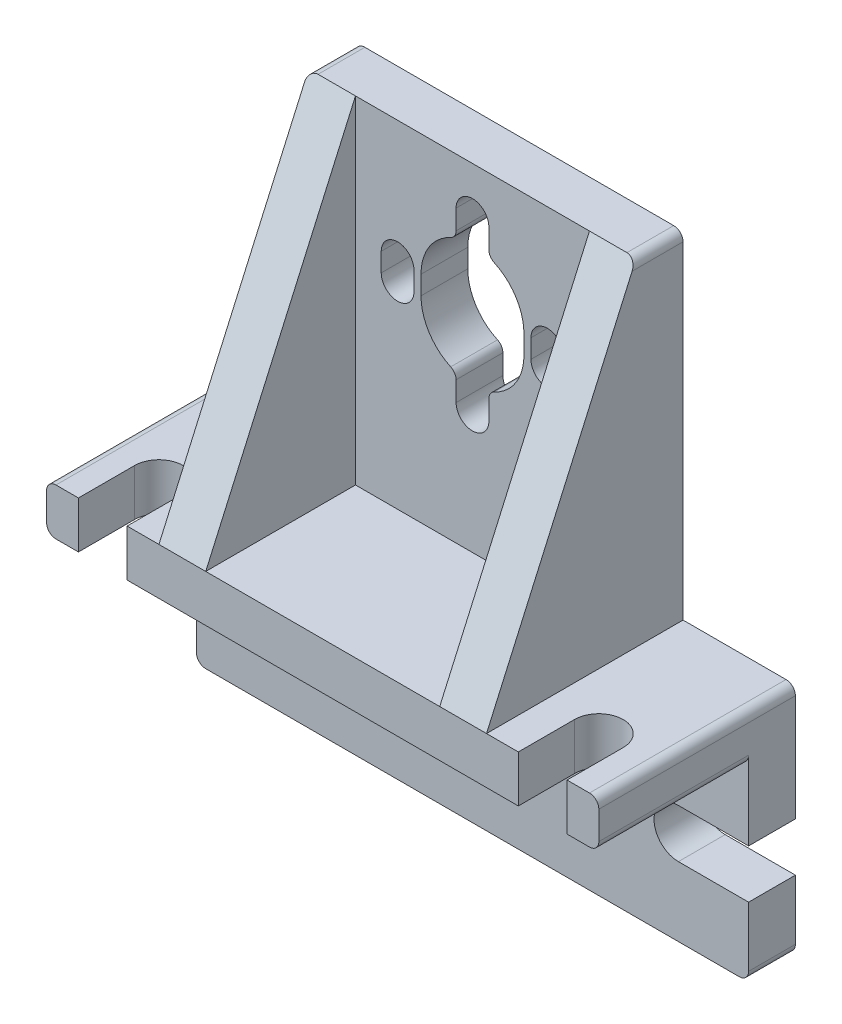
SolidWorks part; units mm, degrees
ref_plane "XY" through (0, 0, 0) normal (0, 0, 1) x (1, 0, 0)
ref_plane "XZ" through (0, 0, 0) normal (0, 1, 0) x (1, 0, 0)
ref_plane "YZ" through (0, 0, 0) normal (1, 0, 0) x (0, 0, -1)
sketch "Sketch1" plane through (0, 0, 0) normal (0, 0, 1) x (1, 0, 0)
  line L0 (0, 30.5) -> (0, -36.5314) construction
  line L1 (-29.5, -30.5) -> (29.5, -30.5)
  line L2 (-29.5, -30.5) -> (-29.5, -23.1)
  line L3 (-29.5, 30.5) -> (-17.5, 30.5) construction
  line L4 (29.5, -30.5) -> (29.5, -23.1)
  line L5 (-29.5, -30.5) -> (29.5, 30.5) construction
  line L6 (-29.5, 30.5) -> (29.5, -30.5) construction
  line L7 (-17.5, 30.5) -> (-17.5, -5.5)
  line L8 (-17.5, -5.5) -> (-29.5, -5.5)
  line L9 (17.5, 30.5) -> (17.5, -5.5)
  line L10 (17.5, -5.5) -> (29.5, -5.5)
  line L11 (-17.5, 30.5) -> (17.5, 30.5)
  line L12 (17.5, 30.5) -> (29.5, 30.5) construction
  line L13 (29.5, -5.5) -> (29.5, 30.5) construction
  line L14 (-29.5, -5.5) -> (-29.5, 30.5) construction
  line L15 (-22, -17.9) -> (-29.5, -17.9)
  line L16 (-22, -23.1) -> (-29.5, -23.1)
  line L17 (0, 25.5) -> (0, 7.5) construction
  line L18 (1.75, 25.5) -> (1.75, 7.5)
  line L19 (-1.75, 25.5) -> (-1.75, 7.5)
  line L20 (0, 17.5) -> (0, 15.5) construction
  line L21 (5.5, 17.5) -> (5.5, 15.5)
  line L22 (-5.5, 17.5) -> (-5.5, 15.5)
  line L23 (-8, 17.5) -> (-8, 15.5) construction
  line L24 (-6.25, 17.5) -> (-6.25, 15.5)
  line L25 (-9.75, 17.5) -> (-9.75, 15.5)
  line L26 (-29.5, -17.9) -> (-29.5, -5.5)
  line L27 (-29.5, -23.1) -> (-29.5, -17.9) construction
  line L28 (22, -23.1) -> (29.5, -23.1)
  line L29 (22, -17.9) -> (29.5, -17.9)
  line L30 (29.5, -17.9) -> (29.5, -5.5)
  line L31 (29.5, -23.1) -> (29.5, -17.9) construction
  line L32 (8, 17.5) -> (8, 15.5) construction
  line L33 (6.25, 17.5) -> (6.25, 15.5)
  line L34 (9.75, 17.5) -> (9.75, 15.5)
  arc A0 (-22, -23.1) -> (-22, -17.9) centre (-22, -20.5) ccw
  arc A1 (1.75, 25.5) -> (-1.75, 25.5) centre (0, 25.5) ccw
  arc A2 (-1.75, 7.5) -> (1.75, 7.5) centre (0, 7.5) ccw
  arc A3 (5.5, 17.5) -> (-5.5, 17.5) centre (0, 17.5) ccw
  arc A4 (-5.5, 15.5) -> (5.5, 15.5) centre (0, 15.5) ccw
  arc A5 (-6.25, 17.5) -> (-9.75, 17.5) centre (-8, 17.5) ccw
  arc A6 (-9.75, 15.5) -> (-6.25, 15.5) centre (-8, 15.5) ccw
  arc A7 (22, -23.1) -> (22, -17.9) centre (22, -20.5) cw
  arc A8 (6.25, 17.5) -> (9.75, 17.5) centre (8, 17.5) cw
  arc A9 (9.75, 15.5) -> (6.25, 15.5) centre (8, 15.5) cw
  point P0 (0, 0)
  point P22 (0, 16.5)
  point P27 (0, 16.5)
  point P34 (-8, 16.5)
  point P47 (8, 16.5)
  dimension "D5" = 5.2
  dimension "D10" = 1.75
  dimension "D14" = 1.75
  dimension "D1" = 59
  dimension "D2" = 61
  dimension "D3" = 36
  dimension "D4" = 12
  dimension "D6" = 20.5
  dimension "D7" = 22
  dimension "D8" = 16.5
  dimension "D9" = 18
  dimension "D11" = 2
  dimension "D12" = 11
  dimension "D13" = 2
  dimension "D15" = 8
extrude "Boss-Extrude1" add sketch "Sketch1" along normal blind 5 contours L28 A7 L29 L30 L10 L9 L11 L7 L8 L26 L15 A0 L16 L2 L1 L4 A6 L25 A5 L24 A4 L22 A3 L19 A1 L18 L21 A2 L34 A9 L33 A8
sketch "Sketch2" plane through (0, 0, 5) normal (0, 0, 1) x (1, 0, 0)
  line L0 (-17.5, 30.5) -> (-12.5, 30.5)
  line L1 (-17.5, 30.5) -> (17.5, 30.5) construction
  line L2 (-12.5, 30.5) -> (-12.5, -5.5)
  line L3 (-12.5, -5.5) -> (12.5, -5.5)
  line L4 (12.5, -5.5) -> (12.5, 30.5)
  line L5 (12.5, 30.5) -> (17.5, 30.5)
  line L6 (17.5, 30.5) -> (17.5, -5.5)
  line L7 (17.5, -5.5) -> (29.5, -5.5)
  line L8 (29.5, -5.5) -> (29.5, -10.5)
  line L9 (29.5, -17.9) -> (29.5, -5.5) construction
  line L10 (29.5, -10.5) -> (-29.5, -10.5)
  line L11 (-29.5, -17.9) -> (-29.5, -5.5) construction
  line L12 (-29.5, -10.5) -> (-29.5, -5.5)
  line L13 (-29.5, -5.5) -> (-17.5, -5.5)
  line L14 (-17.5, -5.5) -> (-17.5, 30.5)
  dimension "D1" = 5
  dimension "D2" = 5
  dimension "D3" = 5
extrude "Boss-Extrude2" add sketch "Sketch2" along normal blind 16
sketch "Sketch3" plane through (17.5, 0, 0) normal (1, 0, 0) x (0, 0, -1)
  line L0 (-21, -5.5) -> (-21, 30.5)
  line L1 (-21, 30.5) -> (-5, 30.5)
  line L2 (-21, 30.5) -> (0, 30.5) construction
  line L3 (-5, 30.5) -> (-21, -5.5)
  dimension "D1" = 16
extrude "Cut-Extrude1" cut sketch "Sketch3" against normal through all
sketch "Sketch4" plane through (0, -10.5, 0) normal (0, -1, 0) x (1, 0, 0)
  line L0 (-26.1, 15) -> (-26.1, 21)
  line L1 (-29.5, 21) -> (29.5, 21) construction
  line L2 (-26.1, 21) -> (-20.9, 21)
  line L3 (-20.9, 21) -> (-20.9, 15)
  line L4 (0, 31.8901) -> (0, -11.7511) construction
  line L5 (20.9, 21) -> (20.9, 15)
  line L6 (26.1, 21) -> (20.9, 21)
  line L7 (26.1, 15) -> (26.1, 21)
  arc A0 (-26.1, 15) -> (-20.9, 15) centre (-23.5, 15) ccw
  arc A1 (26.1, 15) -> (20.9, 15) centre (23.5, 15) cw
  dimension "D1" = 5.2
  dimension "D2" = 15
  dimension "D3" = 23.5
extrude "Cut-Extrude2" cut sketch "Sketch4" against normal blind 16
fillet "Fillet1" radius 1 8 edges at (-17.5, 30.5, 2.5) (17.5, 30.5, 2.5) (29.5, -5.5, 10.5) (29.5, -10.5, 13) (29.5, -30.5, 2.5) (-29.5, -5.5, 10.5) (-29.5, -10.5, 13) (-29.5, -30.5, 2.5)
fillet "Fillet2" radius 1 4 edges at (1.75, 22.7142, 2.5) (-1.75, 22.7142, 2.5) (-1.75, 10.2858, 2.5) (1.75, 10.2858, 2.5)
